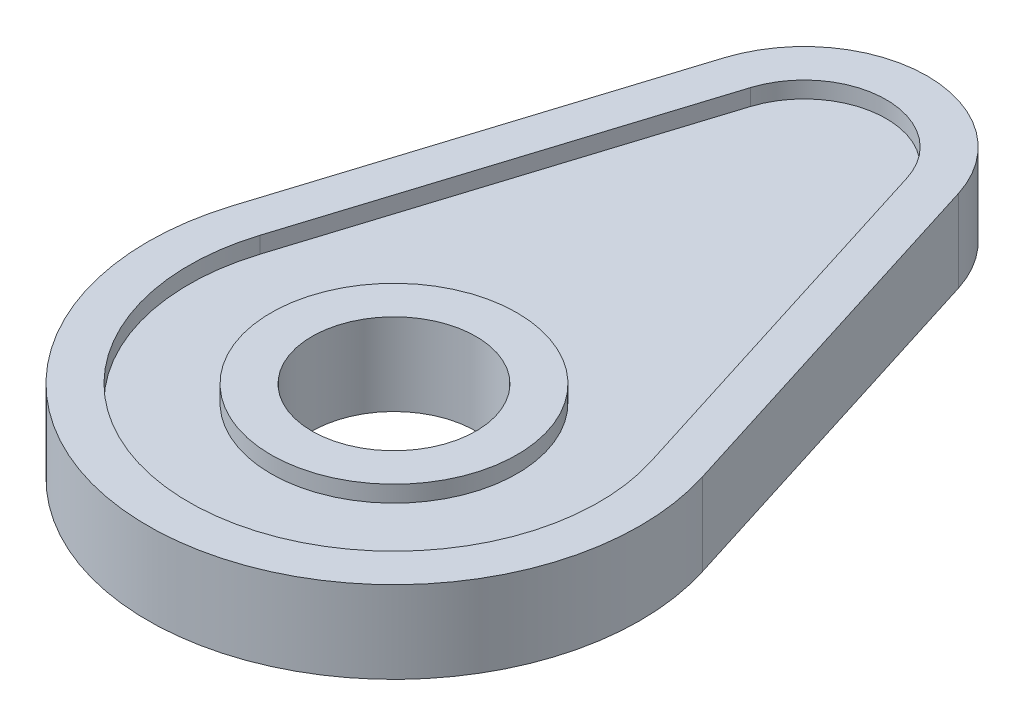
SolidWorks part; units mm, degrees
ref_plane "Front Plane" through (0, 0, 0) normal (0, 0, 1) x (1, 0, 0)
ref_plane "Top Plane" through (0, 0, 0) normal (0, 1, 0) x (1, 0, 0)
ref_plane "Right Plane" through (0, 0, 0) normal (1, 0, 0) x (0, 0, -1)
sketch "Sketch1" plane through (0, 0, 0) normal (0, 1, 0) x (1, 0, 0)
  line L0 (0, 0) -> (0, 50) construction
  line L1 (-28.6182, 9) -> (-14.3091, 54.5)
  line L2 (14.3091, 54.5) -> (28.6182, 9)
  arc A0 (-28.6182, 9) -> (28.6182, 9) centre (0, 0) ccw
  arc A1 (14.3091, 54.5) -> (-14.3091, 54.5) centre (0, 50) ccw
  dimension "D1" = 60
  dimension "D3" = 30
  dimension "D2" = 50
extrude "Boss-Extrude1" add sketch "Sketch1" against normal mid plane 10 contours A0 L2 A1 L1
sketch "Sketch2" plane through (0, 5, 0) normal (0, 1, 0) x (1, 0, 0)
  line L4 (-9.5394, 53) -> (-23.8485, 7.5)
  line L5 (23.8485, 7.5) -> (9.5394, 53)
  line L6 (-9.5394, 53) -> (-23.8485, 7.5)
  line L7 (23.8485, 7.5) -> (9.5394, 53)
  arc A4 (-23.8485, 7.5) -> (23.8485, 7.5) centre (0, 0) ccw
  arc A5 (9.5394, 53) -> (-9.5394, 53) centre (0, 50) ccw
  arc A6 (-23.8485, 7.5) -> (23.8485, 7.5) centre (0, 0) ccw
  arc A7 (9.5394, 53) -> (-9.5394, 53) centre (0, 50) ccw
  dimension "D1" = 5
extrude "Cut-Extrude1" cut sketch "Sketch2" against normal blind 2
mirror "Mirror1" about plane through (0, 0, 0) normal (0, 1, 0) of "Cut-Extrude1"
sketch "Sketch3" plane through (0, 3, 0) normal (0, 1, 0) x (1, 0, 0)
  circle A0 centre (0, 0) radius 10
  dimension "D2" = 20
extrude "Cut-Extrude4" cut sketch "Sketch3" against normal through all
sketch "Sketch5" plane through (0, 3, 0) normal (0, 1, 0) x (1, 0, 0)
  circle A0 centre (0, 0) radius 10 construction
  circle A1 centre (0, 0) radius 10
  circle A2 centre (0, 0) radius 15
  dimension "D1" = 30
extrude "Boss-Extrude2" add sketch "Sketch5" along normal blind 2
mirror "Mirror2" about plane through (0, 0, 0) normal (0, 1, 0) of "Boss-Extrude2"
